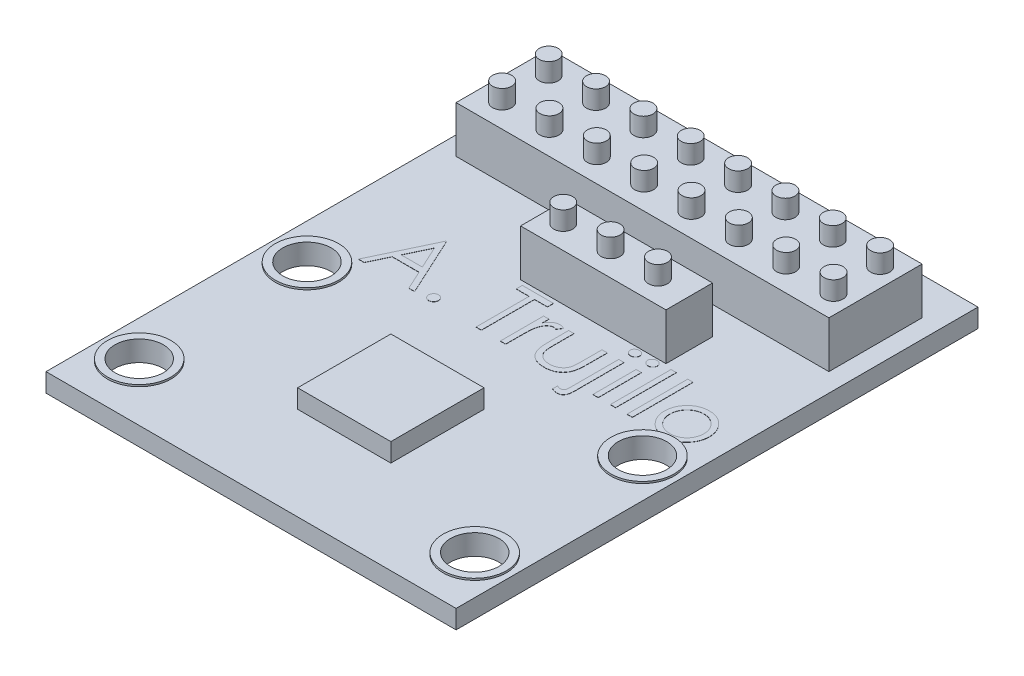
SolidWorks part; units mm, degrees
ref_plane "Front Plane" through (0, 0, 0) normal (0, 0, 1) x (1, 0, 0)
ref_plane "Top Plane" through (0, 0, 0) normal (0, 1, 0) x (1, 0, 0)
ref_plane "Right Plane" through (0, 0, 0) normal (1, 0, 0) x (0, 0, -1)
sketch "Sketch1" plane through (0, 0, 0) normal (0, 1, 0) x (1, 0, 0)
  line L1 (-11, 14) -> (11, 14)
  line L2 (-11, 14) -> (-11, -14)
  line L3 (-11, -14) -> (11, -14)
  line L4 (11, 14) -> (11, -14)
  line L5 (-11, 14) -> (11, -14) construction
  line L6 (-11, -14) -> (11, 14) construction
  point P0 (0, 0)
  dimension "D1" = 22
  dimension "D2" = 28
extrude "Boss-Extrude1" add sketch "Sketch1" along normal blind 1
sketch "Sketch2" plane through (0, 1, 0) normal (0, 1, 0) x (1, 0, 0)
  line L1 (-10, 12) -> (10, 12)
  line L2 (-10, 12) -> (-10, 7)
  line L3 (-10, 7) -> (10, 7)
  line L4 (10, 12) -> (10, 7)
  dimension "D1" = 10
  dimension "D2" = 7
  dimension "D3" = 5
  dimension "D4" = 20
extrude "Boss-Extrude2" add sketch "Sketch2" along normal blind 2.5
sketch "Sketch3" plane through (0, 3.5, 0) normal (0, 1, 0) x (1, 0, 0)
  line L0 (10, 9.5) -> (-10, 9.5) construction
  line L1 (10, 7) -> (10, 12) construction
  line L2 (-10, 12) -> (-10, 7) construction
  circle A0 centre (9, 8.25) radius 0.51
  circle A1 centre (6.46, 8.25) radius 0.51
  circle A2 centre (3.92, 8.25) radius 0.51
  circle A3 centre (1.38, 8.25) radius 0.51
  circle A4 centre (-1.16, 8.25) radius 0.51
  circle A5 centre (-3.7, 8.25) radius 0.51
  circle A6 centre (-6.24, 8.25) radius 0.51
  circle A7 centre (-8.78, 8.25) radius 0.51
  circle A8 centre (-8.78, 10.75) radius 0.51
  circle A9 centre (-6.24, 10.75) radius 0.51
  circle A10 centre (-3.7, 10.75) radius 0.51
  circle A11 centre (-1.16, 10.75) radius 0.51
  circle A12 centre (1.38, 10.75) radius 0.51
  circle A13 centre (3.92, 10.75) radius 0.51
  circle A14 centre (6.46, 10.75) radius 0.51
  circle A15 centre (9, 10.75) radius 0.51
  dimension "D1" = 1.02
  dimension "D2" = 9
  dimension "D3" = 8.25
  dimension "D4" = 8
extrude "Boss-Extrude3" add sketch "Sketch3" along normal blind 1
sketch "Sketch4" plane through (0, 1, 0) normal (0, 1, 0) x (1, 0, 0)
  line L1 (2.5, -9) -> (-2.5, -9)
  line L2 (2.5, -9) -> (2.5, -4)
  line L3 (2.5, -4) -> (-2.5, -4)
  line L4 (-2.5, -9) -> (-2.5, -4)
  point P4 (0, -4)
  dimension "D1" = 4
  dimension "D2" = 5
  dimension "D3" = 5
extrude "Boss-Extrude4" add sketch "Sketch4" along normal blind 1
sketch "Sketch5" plane through (0, 1, 0) normal (0, 1, 0) x (1, 0, 0)
  line L0 (0, 0) -> (0, -14) construction
  line L1 (-11, -14) -> (11, -14) construction
  line L2 (-11, -6.5) -> (11, -6.5) construction
  line L5 (-11, 14) -> (-11, -14) construction
  line L6 (11, -14) -> (11, 14) construction
  line L7 (-2.5, -4) -> (-2.5, -9) construction
  circle A0 centre (-9, -2) radius 1.3
  circle A1 centre (9, -2) radius 1.3
  circle A2 centre (9, -11) radius 1.3
  circle A3 centre (-9, -11) radius 1.3
  point P21 (-2.5, -6.5)
  dimension "D1" = 2.6
  dimension "D2" = 9
  dimension "D3" = 2
extrude "Cut-Extrude1" cut sketch "Sketch5" against normal blind 1
sketch "Sketch6" plane through (0, 1, 0) normal (0, 1, 0) x (1, 0, 0)
  circle A0 centre (-9, -11) radius 1.3 construction
  circle A1 centre (9, -11) radius 1.3 construction
  circle A2 centre (9, -2) radius 1.3 construction
  circle A3 centre (-9, -2) radius 1.3 construction
  circle A4 centre (-9, -11) radius 1.3
  circle A5 centre (9, -11) radius 1.3
  circle A6 centre (9, -2) radius 1.3
  circle A7 centre (-9, -2) radius 1.3
  circle A8 centre (-9, -2) radius 1.7
  circle A9 centre (9, -2) radius 1.7
  circle A10 centre (-9, -11) radius 1.7
  circle A11 centre (9, -11) radius 1.7
  dimension "D1" = 3.4
  dimension "D2" = 3.4
  dimension "D3" = 3.4
  dimension "D4" = 3.4
extrude "Boss-Extrude5" add sketch "Sketch6" along normal blind 0.1
sketch "Sketch7" plane through (0, 1, 0) normal (0, 1, 0) x (1, 0, 0)
  line L1 (-2.54, 5.5) -> (5.26, 5.5)
  line L2 (-2.54, 5.5) -> (-2.54, 3)
  line L3 (-2.54, 3) -> (5.26, 3)
  line L4 (5.26, 5.5) -> (5.26, 3)
  dimension "D1" = 2.5
  dimension "D2" = 7.8
  dimension "D3" = 3
  dimension "D4" = 2.54
extrude "Boss-Extrude6" add sketch "Sketch7" along normal blind 2.5
sketch "Sketch8" plane through (0, 3.5, 0) normal (0, 1, 0) x (1, 0, 0)
  line L0 (-2.54, 5.5) -> (-2.54, 3) construction
  circle A0 centre (-1.5, 4.25) radius 0.51
  circle A1 centre (1.04, 4.25) radius 0.51
  circle A2 centre (3.58, 4.25) radius 0.51
  point P5 (-2.54, 4.25)
  dimension "D3" = 1.02
  dimension "D1" = 1.5
  dimension "D2" = 3
extrude "Boss-Extrude7" add sketch "Sketch8" along normal blind 1
sketch "Sketch9" plane through (0, 1, 0) normal (0, 1, 0) x (1, 0, 0)
  text T0 "A. Trujillo"
  dimension "D1" = 8
  dimension "D2" = 3.6
extrude "Boss-Extrude8" add sketch "Sketch9" along normal blind 0.01
